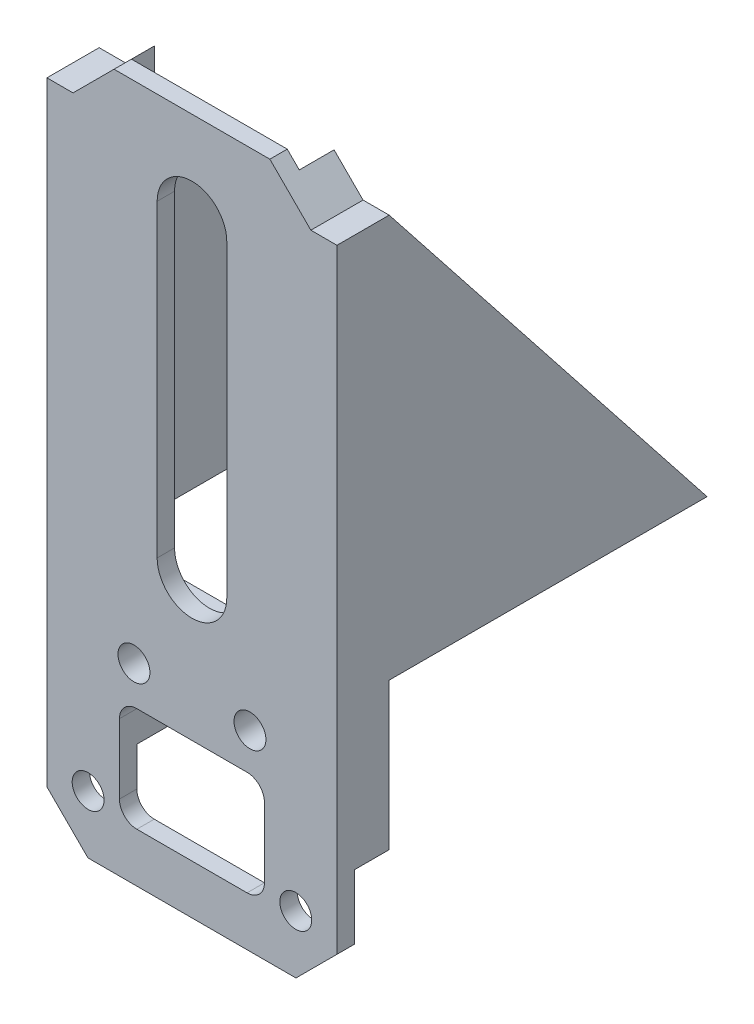
SolidWorks part; units mm, degrees
ref_plane "Front Plane" through (0, 0, 0) normal (0, 0, 1) x (1, 0, 0)
ref_plane "Top Plane" through (0, 0, 0) normal (0, 1, 0) x (1, 0, 0)
ref_plane "Right Plane" through (0, 0, 0) normal (1, 0, 0) x (0, 0, -1)
sketch "Sketch1" plane through (0, 0, 0) normal (0, 0, 1) x (1, 0, 0)
  line L0 (25, 120) -> (25, 0) construction
  line L1 (7.0711, 0) -> (42.9289, 0)
  line L2 (0, 7.0711) -> (0, 43.5)
  line L3 (11.5711, 120) -> (38.4289, 120)
  line L4 (50, 7.0711) -> (50, 43.5)
  line L5 (25, 50.75) -> (25, 104) construction
  line L6 (19, 50.75) -> (19, 104)
  line L7 (31, 50.75) -> (31, 104)
  line L8 (0, 10) -> (50, 10) construction
  line L12 (4.5, 112.9289) -> (4.5, 48)
  line L13 (4.5, 48) -> (0, 43.5)
  line L14 (45.5, 48) -> (50, 43.5)
  line L15 (45.5, 112.9289) -> (45.5, 48)
  line L16 (11.5711, 120) -> (4.5, 112.9289)
  line L17 (38.4289, 120) -> (45.5, 112.9289)
  line L18 (0, 7.0711) -> (7.0711, 0)
  line L19 (50, 7.0711) -> (42.9289, 0)
  line L20 (0, 7.0711) -> (0, 0) construction
  line L21 (12.5, 26.5) -> (37.5, 26.5)
  line L22 (0, 0) -> (7.0711, 0) construction
  line L23 (37.5, 26.5) -> (37.5, 8.5)
  line L24 (37.5, 8.5) -> (12.5, 8.5)
  line L25 (12.5, 26.5) -> (12.5, 8.5)
  arc A0 (19, 50.75) -> (31, 50.75) centre (25, 50.75) ccw
  arc A1 (31, 104) -> (19, 104) centre (25, 104) ccw
  circle A2 centre (7.1, 10) radius 2.75
  circle A3 centre (42.9, 10) radius 2.75
  point P9 (25, 77.375)
  point P39 (25, 26.5)
  point P42 (25, 8.5)
  dimension "D6" = 5.5
  dimension "D10" = 32
  dimension "D3" = 10
  dimension "D1" = 50
  dimension "D2" = 120
  dimension "D4" = 12
  dimension "D5" = 35.8
  dimension "D7" = 10
  dimension "D8" = 18
  dimension "D9" = 8.5
  dimension "D11" = 135
  dimension "D12" = 43.5
  dimension "D13" = 41
  dimension "D14" = 135
  dimension "D15" = 10
  dimension "D16" = 135
  dimension "D17" = 10
  dimension "D18" = 25
extrude "Boss-Extrude1" add sketch "Sketch1" along normal blind 3
sketch "Sketch3" plane through (0, 0, 3) normal (0, 0, 1) x (1, 0, 0)
  line L0 (25, 44.75) -> (25, 14) construction
  circle A0 centre (15, 33) radius 2.75
  arc A1 (19, 50.75) -> (31, 50.75) centre (25, 50.75) ccw construction
  circle A2 centre (35, 33) radius 2.75
  circle A3 centre (7.1, 10) radius 2.75 construction
  dimension "D1" = 5.5
  dimension "D2" = 23
  dimension "D3" = 20
extrude "Cut-Extrude1" cut sketch "Sketch3" against normal up to next
sketch "Sketch2" plane through (0, 0, 0) normal (0, 0, -1) x (-1, 0, 0)
  line L0 (-50, 18.19) -> (-37.5, 18.19)
  line L1 (-50, 7.0711) -> (-50, 43.5) construction
  line L2 (0, 43.5) -> (0, 7.0711) construction
  line L7 (-50, 43.5) -> (-50, 18.19)
  line L9 (0, 43.5) -> (0, 18.19)
  line L10 (-7.0711, 0) -> (-42.9289, 0) construction
  line L11 (-4.5, 112.9289) -> (-4.5, 48)
  line L12 (-9.5, 117.9289) -> (-9.5, 40.75)
  line L13 (-11.5711, 120) -> (-4.5, 112.9289) construction
  line L14 (-4.5, 112.9289) -> (-9.5, 117.9289)
  line L16 (-45.5, 112.9289) -> (-45.5, 48)
  line L17 (-40.5, 117.9289) -> (-40.5, 40.75)
  line L18 (-45.5, 112.9289) -> (-38.4289, 120) construction
  line L19 (-40.5, 117.9289) -> (-45.5, 112.9289)
  line L21 (-40.5, 40.75) -> (-9.5, 40.75)
  line L22 (-37.5, 18.19) -> (-37.5, 26.5)
  line L23 (-37.5, 26.5) -> (-12.5, 26.5)
  line L24 (-12.5, 26.5) -> (-12.5, 18.19)
  line L25 (-37.5, 8.5) -> (-37.5, 26.5) construction
  line L26 (-37.5, 26.5) -> (-12.5, 26.5) construction
  line L27 (-12.5, 26.5) -> (-12.5, 8.5) construction
  line L28 (-12.5, 18.19) -> (0, 18.19)
  line L31 (-45.5, 48) -> (-50, 43.5)
  line L32 (-4.5, 48) -> (0, 43.5)
  circle A0 centre (-35, 33) radius 2.75
  circle A1 centre (-15, 33) radius 2.75
  arc A2 (-31, 50.75) -> (-19, 50.75) centre (-25, 50.75) ccw construction
  dimension "D5" = 5.5
  dimension "D1" = 10
  dimension "D2" = 18.19
  dimension "D3" = 5
  dimension "D4" = 5
extrude "Boss-Extrude2" add sketch "Sketch2" along normal blind 6
fillet "Fillet1" radius 3 4 edges at (37.5, 8.5, 1.5) (37.5, 26.5, -1.5) (12.5, 26.5, -1.5) (12.5, 8.5, 1.5)
sketch "Sketch4" plane through (45.5, 0, 0) normal (1, 0, 0) x (0, 0, -1)
  line L1 (-3, 43.5) -> (60.8, 43.5)
  line L2 (60.8, 43.5) -> (6, 112.9289)
  line L3 (-3, 43.5) -> (6, 43.5) construction
  line L4 (6, 112.9289) -> (-3, 112.9289)
  line L5 (-3, 112.9289) -> (-3, 43.5)
  point P6 (-3, 43.5)
  point P10 (-3, 43.3441)
  dimension "D1" = 63.8
extrude "Boss-Extrude5" add sketch "Sketch4" along normal blind 4.5
sketch "Sketch7" plane through (4.5, 0, 0) normal (-1, 0, 0) x (0, 0, 1)
  line L0 (3, 112.9289) -> (3, 43.5)
  line L1 (3, 112.9289) -> (3, 48) construction
  line L2 (3, 112.9289) -> (-6, 112.9289)
  line L3 (-6, 112.9289) -> (-60.8, 43.5)
  line L4 (-60.8, 43.5) -> (3, 43.5)
  line L5 (-6, 43.5) -> (-60.8, 43.5) construction
  line L6 (-60.8, 43.5) -> (-6, 112.9289) construction
extrude "Boss-Extrude6" add sketch "Sketch7" along normal blind 4.5
